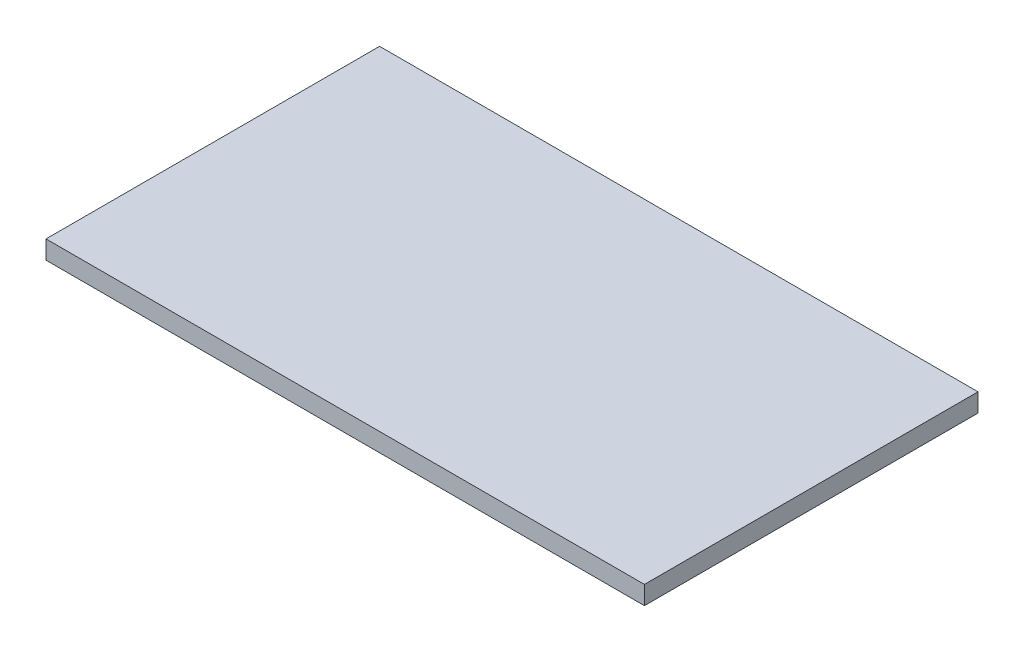
SolidWorks part; units mm, degrees
ref_plane "Front Plane" through (0, 0, 0) normal (0, 0, 1) x (1, 0, 0)
ref_plane "Top Plane" through (0, 0, 0) normal (0, 1, 0) x (1, 0, 0)
ref_plane "Right Plane" through (0, 0, 0) normal (1, 0, 0) x (0, 0, -1)
sketch "Sketch1" plane through (0, 0, 0) normal (0, 1, 0) x (1, 0, 0)
  line L0 (-77.05, -42.95) -> (77.05, -42.95)
  line L1 (-77.05, -42.95) -> (-77.05, 42.95)
  line L2 (77.05, -42.95) -> (77.05, 42.95)
  line L3 (-77.05, 42.95) -> (77.05, 42.95)
  line L4 (-77.05, -42.95) -> (77.05, 42.95) construction
  line L5 (77.05, -42.95) -> (-77.05, 42.95) construction
  point P1 (0, 0)
  dimension "D1" = 154.1
  dimension "D2" = 85.9
extrude "Boss-Extrude1" add sketch "Sketch1" along normal blind 4.75
